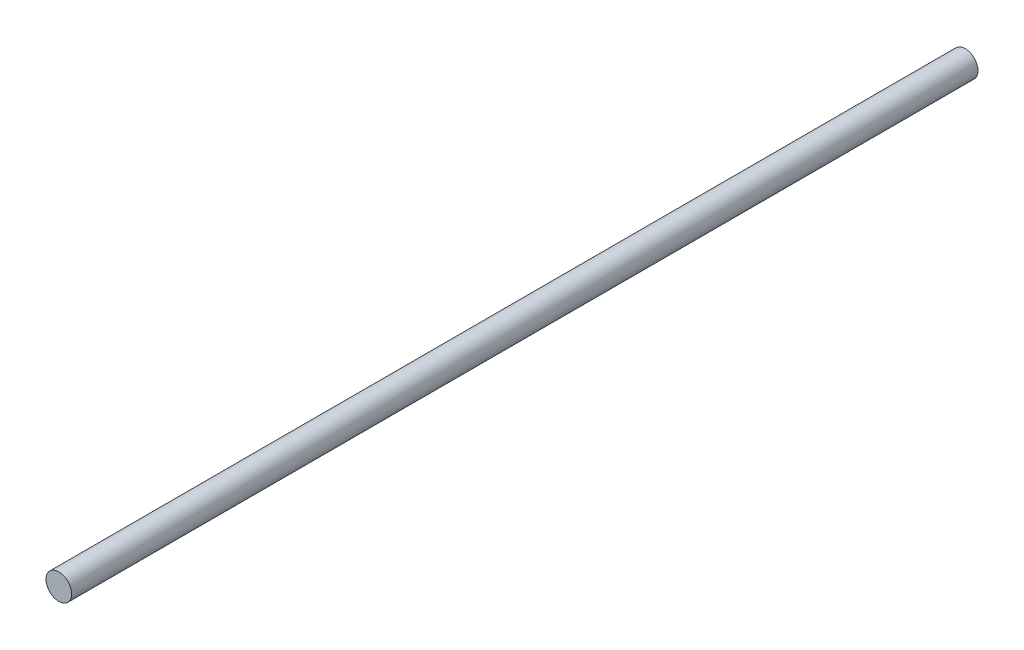
SolidWorks part; units mm, degrees
material "LW-PLA"
ref_plane "Front Plane" through (0, 0, 0) normal (0, 0, 1) x (1, 0, 0)
ref_plane "Top Plane" through (0, 0, 0) normal (0, 1, 0) x (1, 0, 0)
ref_plane "Right Plane" through (0, 0, 0) normal (1, 0, 0) x (0, 0, -1)
sketch "Sketch1" plane through (0, 0, 0) normal (0, 0, 1) x (1, 0, 0)
  circle A0 centre (0, 0) radius 0.75
  dimension "D1" = 1.5
extrude "Boss-Extrude1" add sketch "Sketch1" along normal blind 53
